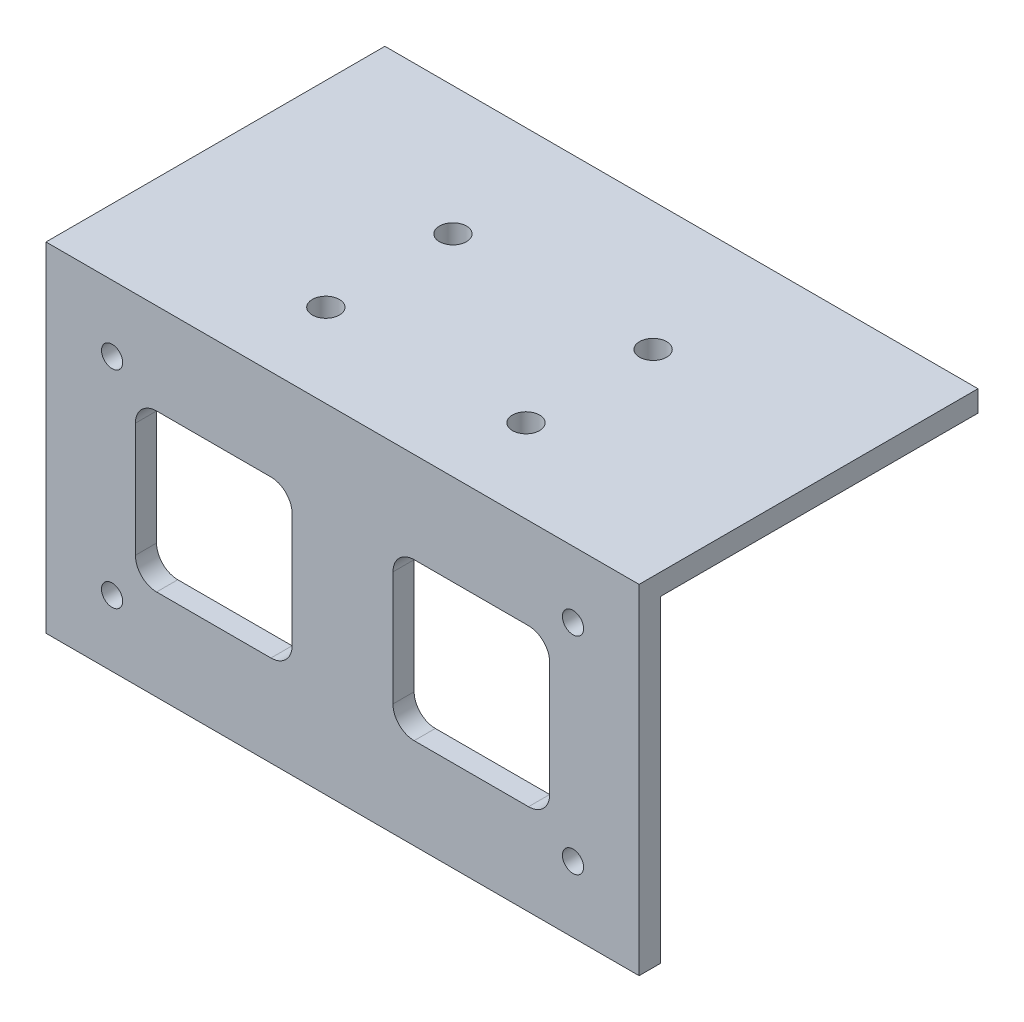
SolidWorks part; units mm, degrees
ref_plane "前视基准面" through (0, 0, 0) normal (0, 0, 1) x (1, 0, 0)
ref_plane "上视基准面" through (0, 0, 0) normal (0, 1, 0) x (1, 0, 0)
ref_plane "右视基准面" through (0, 0, 0) normal (1, 0, 0) x (0, 0, -1)
sketch "Sketch1" plane through (0, 0, 0) normal (0, 0, 1) x (1, 0, 0)
  line L0 (-76.2, 0) -> (-1.016, 0) construction
  line L1 (76.2, -38.1) -> (-76.2, -38.1) construction
  line L2 (76.2, -38.1) -> (76.2, 38.1) construction
  line L3 (76.2, 38.1) -> (-76.2, 38.1) construction
  line L4 (-76.2, -38.1) -> (-76.2, 38.1) construction
  line L5 (76.2, -38.1) -> (-76.2, 38.1) construction
  line L6 (76.2, 38.1) -> (-76.2, -38.1) construction
  line L7 (-88.9, 50.8) -> (-88.9, -50.8)
  line L8 (-76.2, 38.1) -> (76.2, 38.1)
  line L9 (88.9, 50.8) -> (88.9, -50.8)
  line L10 (-88.9, 50.8) -> (88.9, 50.8)
  line L11 (0, 50.8) -> (0, 38.1) construction
  line L12 (-76.2, -38.1) -> (76.2, -38.1)
  line L14 (-88.9, -50.8) -> (88.9, -50.8)
  line L15 (-62.103, 23.495) -> (-15.113, 23.495)
  line L16 (-62.103, 23.495) -> (-62.103, -23.495)
  line L17 (-62.103, -23.495) -> (-15.113, -23.495)
  line L18 (-15.113, 23.495) -> (-15.113, -23.495)
  line L19 (15.113, 23.495) -> (62.103, 23.495)
  line L20 (15.113, 23.495) -> (15.113, -23.495)
  line L21 (15.113, -23.495) -> (62.103, -23.495)
  line L22 (62.103, 23.495) -> (62.103, -23.495)
  circle A0 centre (-69.088, 30.988) radius 3.175
  circle A1 centre (69.088, 30.988) radius 3.175
  circle A2 centre (69.088, -30.988) radius 3.175
  circle A3 centre (-69.088, -30.988) radius 3.175
  circle A4 centre (-38.608, 0) radius 23.495 construction
  circle A5 centre (38.608, 0) radius 23.495 construction
  point P0 (0, 0)
  dimension "D7" = 6.35
  dimension "D8" = 6.35
  dimension "D11" = 46.99
  dimension "D12" = 46.99
  dimension "D1" = 76.2
  dimension "D2" = 152.4
  dimension "D3" = 30.988
  dimension "D4" = 30.988
  dimension "D5" = 69.088
  dimension "D6" = 69.088
  dimension "D9" = 38.608
  dimension "D10" = 38.608
  dimension "D13" = 12.7
  dimension "D14" = 101.6
  dimension "D15" = 12.7
extrude "Boss-Extrude2" add sketch "Sketch1" along normal blind 6.35
sketch "Sketch2" plane through (0, 0, 0) normal (0, 0, -1) x (-1, 0, 0)
  line L1 (-88.9, 50.8) -> (88.9, 50.8)
  line L2 (-88.9, 50.8) -> (-88.9, 44.45)
  line L3 (-88.9, 44.45) -> (88.9, 44.45)
  line L4 (88.9, 50.8) -> (88.9, 44.45)
  line L5 (-88.9, 50.8) -> (-88.9, -50.8) construction
  line L6 (88.9, 50.8) -> (88.9, -50.8) construction
  line L7 (88.9, 50.8) -> (-88.9, 50.8) construction
  dimension "D1" = 6.35
extrude "Boss-Extrude3" add sketch "Sketch2" along normal blind 95.25
sketch "Sketch3" plane through (0, 50.8, 0) normal (0, 1, 0) x (1, 0, 0)
  line L0 (0, 95.25) -> (0, -6.35) construction
  line L1 (-88.9, 95.25) -> (88.9, 95.25) construction
  line L2 (-88.9, -6.35) -> (88.9, -6.35) construction
  circle A0 centre (-30, 18.65) radius 4.065
  circle A1 centre (-30, 56.75) radius 4.065
  circle A2 centre (30, 18.65) radius 4.065
  circle A3 centre (30, 56.75) radius 4.065
  dimension "D5" = 8.13
  dimension "D1" = 25
  dimension "D2" = 38.1
  dimension "D3" = 30
  dimension "D4" = 30
fillet "Fillet1" radius 6.35 8 edges at (-62.103, -23.495, 3.175) (15.113, -23.495, 3.175) (15.113, 23.495, 3.175) (62.103, 23.495, 3.175) (62.103, -23.495, 3.175) (-15.113, -23.495, 3.175) (-15.113, 23.495, 3.175) (-62.103, 23.495, 3.175)
extrude "Cut-Extrude1" cut sketch "Sketch3" against normal blind 152.4
